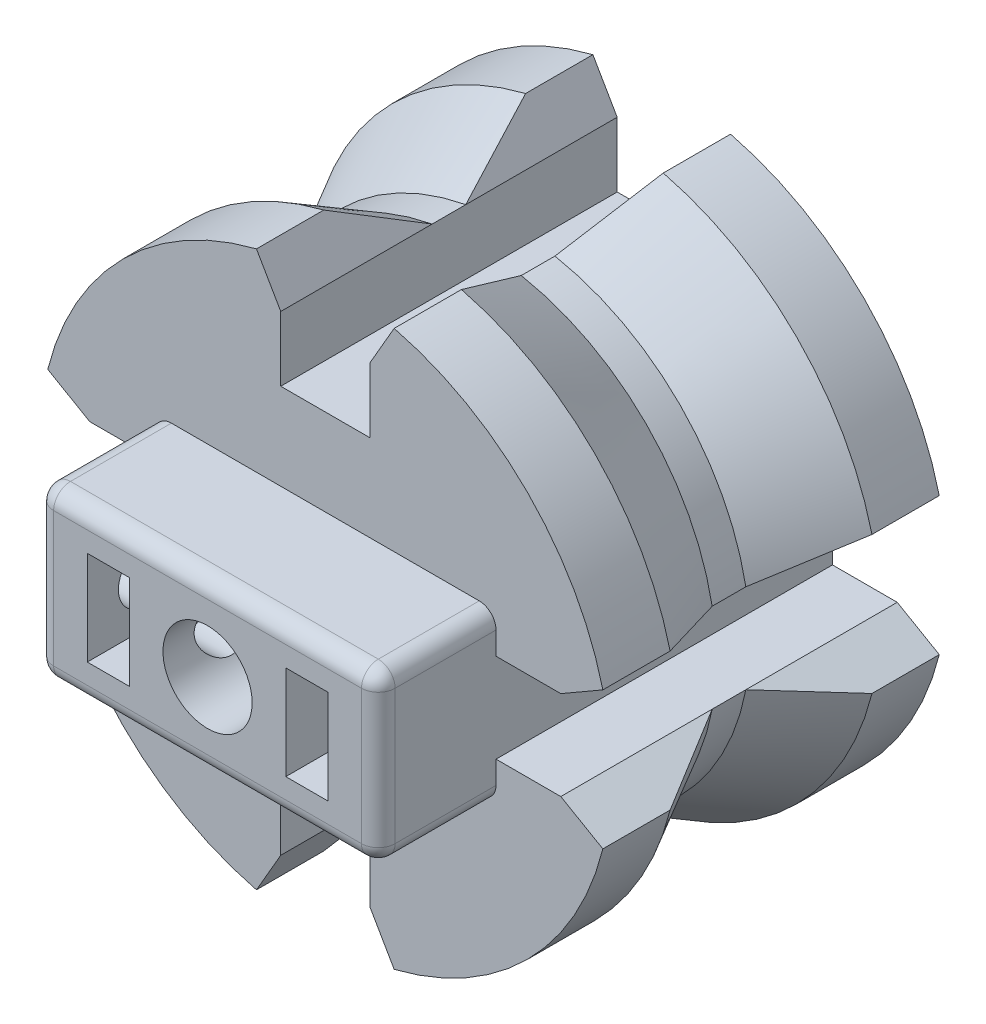
SolidWorks part; units mm, degrees
ref_plane "Front Plane" through (0, 0, 0) normal (0, 0, 1) x (1, 0, 0)
ref_plane "Top Plane" through (0, 0, 0) normal (0, 1, 0) x (1, 0, 0)
ref_plane "Right Plane" through (0, 0, 0) normal (1, 0, 0) x (0, 0, -1)
sketch "Sketch1" plane through (0, 0, 0) normal (0, 0, 1) x (1, 0, 0)
  line L0 (0, 0) -> (0, 21.5251) construction
  line L1 (4.0927, 16.5) -> (2.6493, 14)
  line L2 (2.6493, 14) -> (-2.6493, 14)
  line L3 (-4.0927, 16.5) -> (-2.6493, 14)
  line L4 (16.5, -4.0927) -> (14, -2.6493)
  line L5 (14, -2.6493) -> (14, 2.6493)
  line L6 (16.5, 4.0927) -> (14, 2.6493)
  line L7 (-4.0927, -16.5) -> (-2.6493, -14)
  line L8 (-2.6493, -14) -> (2.6493, -14)
  line L9 (4.0927, -16.5) -> (2.6493, -14)
  line L10 (-16.5, 4.0927) -> (-14, 2.6493)
  line L11 (-14, 2.6493) -> (-14, -2.6493)
  line L12 (-16.5, -4.0927) -> (-14, -2.6493)
  arc A0 (-16.5, -4.0927) -> (-4.0927, -16.5) centre (0, 0) ccw
  circle A1 centre (0, 0) radius 2.65
  arc A2 (-4.0927, 16.5) -> (-16.5, 4.0927) centre (0, 0) ccw
  arc A3 (16.5, 4.0927) -> (4.0927, 16.5) centre (0, 0) ccw
  arc A4 (4.0927, -16.5) -> (16.5, -4.0927) centre (0, 0) ccw
  point P9 (0, 14)
  point P25 (0, 0)
  dimension "D1" = 34
  dimension "D2" = 5.3
  dimension "D3" = 14
  dimension "D4" = 60
  dimension "D5" = 2.5
  dimension "D6" = 4
extrude "Boss-Extrude1" add sketch "Sketch1" along normal blind 20
sketch "Sketch2" plane through (0, 0, 20) normal (0, 0, 1) x (1, 0, 0)
  line L0 (0, 0) -> (0, 12.6789) construction
  line L1 (-10.15, -5) -> (10.15, -5)
  line L2 (-10.15, -5) -> (-10.15, 5)
  line L3 (-10.15, 5) -> (10.15, 5)
  line L4 (10.15, -5) -> (10.15, 5)
  line L5 (-10.15, -5) -> (10.15, 5) construction
  line L6 (-10.15, 5) -> (10.15, -5) construction
  line L7 (-7.15, 2.8) -> (-4.65, 2.8)
  line L8 (-7.15, 2.8) -> (-7.15, -2.8)
  line L9 (-7.15, -2.8) -> (-4.65, -2.8)
  line L10 (-4.65, 2.8) -> (-4.65, -2.8)
  line L11 (-7.15, 2.8) -> (-4.65, -2.8) construction
  line L12 (-7.15, -2.8) -> (-4.65, 2.8) construction
  line L13 (7.15, -2.8) -> (4.65, -2.8)
  line L14 (4.65, 2.8) -> (4.65, -2.8)
  line L15 (7.15, 2.8) -> (4.65, 2.8)
  line L16 (7.15, 2.8) -> (7.15, -2.8)
  circle A3 centre (0, 0) radius 2.65 construction
  circle A4 centre (0, 0) radius 2.65
  point P0 (0, 0)
  point P6 (-5.9, 0)
  dimension "D1" = 2
  dimension "D2" = 10
  dimension "D3" = 3
  dimension "D4" = 2.5
  dimension "D5" = 5.6
extrude "Boss-Extrude2" add sketch "Sketch2" along normal blind 7
sketch "Sketch3" plane through (-10.15, 0, 0) normal (-1, 0, 0) x (0, 0, 1)
  line L0 (27, 5) -> (20, 5) construction
  line L2 (27, 5) -> (27, -5) construction
  circle A0 centre (23.5, 0) radius 1.65
  dimension "D3" = 3.3
  dimension "D1" = 5
  dimension "D2" = 3.5
extrude "Cut-Extrude5" cut sketch "Sketch3" against normal blind 10
fillet "Fillet1" radius 1 8 edges at (10.15, 5, 23.5) (10.15, -5, 23.5) (10.15, 0, 27) (0, 5, 27) (0, -5, 27) (-10.15, 0, 27) (-10.15, 5, 23.5) (-10.15, -5, 23.5)
sketch "Sketch5" plane through (-4.0752, 2.3528, 0) normal (-0.866, 0.5, 0) x (0, 0, 1)
  line L0 (9, 13.449) -> (11, 13.449)
  line L1 (20, 13.449) -> (0, 13.449) construction
  line L2 (20, 16.3358) -> (20, 13.449) construction
  line L4 (11, 13.449) -> (16, 16.3358)
  line L5 (20, 16.3358) -> (0, 16.3358) construction
  line L6 (10, 13.449) -> (10, 16.8131) construction
  line L7 (9, 13.449) -> (4, 16.3358)
  line L8 (4, 16.3358) -> (16, 16.3358)
  point P5 (10, 13.449)
  dimension "D1" = 2
  dimension "D2" = 10
  dimension "D3" = 30
sketch "Sketch6" plane through (0, 0, 20) normal (0, 0, 1) x (1, 0, 0)
  circle A0 centre (0, 0) radius 17
sweep "Cut-Sweep2" cut profiles "Sketch5" path "Sketch6"
sketch "Sketch4" plane through (0, 0, 0) normal (0, 0, -1) x (-1, 0, 0)
  line L0 (-14.6874, -3.0462) -> (-16.5, -4.0927)
  line L1 (-16.5, -4.0927) -> (-14, -2.6493) construction
  line L2 (-3.0462, -14.6874) -> (-4.0927, -16.5)
  line L3 (-2.6493, -14) -> (-4.0927, -16.5) construction
  line L4 (-14.6874, 3.0462) -> (-16.5, 4.0927)
  line L5 (-3.0462, 14.6874) -> (-4.0927, 16.5)
  line L6 (3.0462, 14.6874) -> (4.0927, 16.5)
  line L7 (14.6874, 3.0462) -> (16.5, 4.0927)
  line L8 (14.6874, -3.0462) -> (16.5, -4.0927)
  line L9 (3.0462, -14.6874) -> (4.0927, -16.5)
  arc A0 (-16.5, -4.0927) -> (-4.0927, -16.5) centre (0, 0) ccw
  arc A1 (-4.0927, 16.5) -> (-16.5, 4.0927) centre (0, 0) ccw
  arc A2 (-3.0462, 14.6874) -> (-14.6874, 3.0462) centre (0, 0) ccw
  arc A3 (16.5, 4.0927) -> (4.0927, 16.5) centre (0, 0) ccw
  arc A5 (-14.6874, -3.0462) -> (-3.0462, -14.6874) centre (0, 0) ccw
  circle A6 centre (0, 0) radius 17 construction
  circle A7 centre (0, 0) radius 15 construction
  arc A8 (14.6874, 3.0462) -> (3.0462, 14.6874) centre (0, 0) ccw
  arc A9 (4.0927, -16.5) -> (16.5, -4.0927) centre (0, 0) ccw
  arc A10 (3.0462, -14.6874) -> (14.6874, -3.0462) centre (0, 0) ccw
  point P30 (0, 0)
  dimension "D1" = 2
  dimension "D2" = 4
sketch "Sketch7" plane through (0, 0, 20) normal (0, 0, 1) x (1, 0, 0)
  line L5 (-10.15, 4) -> (-10.15, -4) construction
  line L6 (-14, -2.6493) -> (-10.15, -2.6493)
  line L7 (-14, -2.6493) -> (-14, 2.6493)
  line L8 (-14, 2.6493) -> (-10.15, 2.6493)
  line L9 (-10.15, -2.6493) -> (-10.15, 2.6493)
  line L10 (-2.6493, 14) -> (2.6493, 14)
  line L11 (-2.6493, 14) -> (-2.6493, 10.15)
  line L12 (-2.6493, 10.15) -> (2.6493, 10.15)
  line L13 (2.6493, 14) -> (2.6493, 10.15)
  line L14 (14, 2.6493) -> (14, -2.6493)
  line L15 (14, 2.6493) -> (10.15, 2.6493)
  line L16 (10.15, 2.6493) -> (10.15, -2.6493)
  line L17 (14, -2.6493) -> (10.15, -2.6493)
  line L18 (2.6493, -14) -> (-2.6493, -14)
  line L19 (2.6493, -14) -> (2.6493, -10.15)
  line L20 (2.6493, -10.15) -> (-2.6493, -10.15)
  line L21 (-2.6493, -14) -> (-2.6493, -10.15)
  point P23 (0, 0)
  dimension "D1" = 4
extrude "Cut-Extrude6" cut sketch "Sketch7" against normal blind 20
